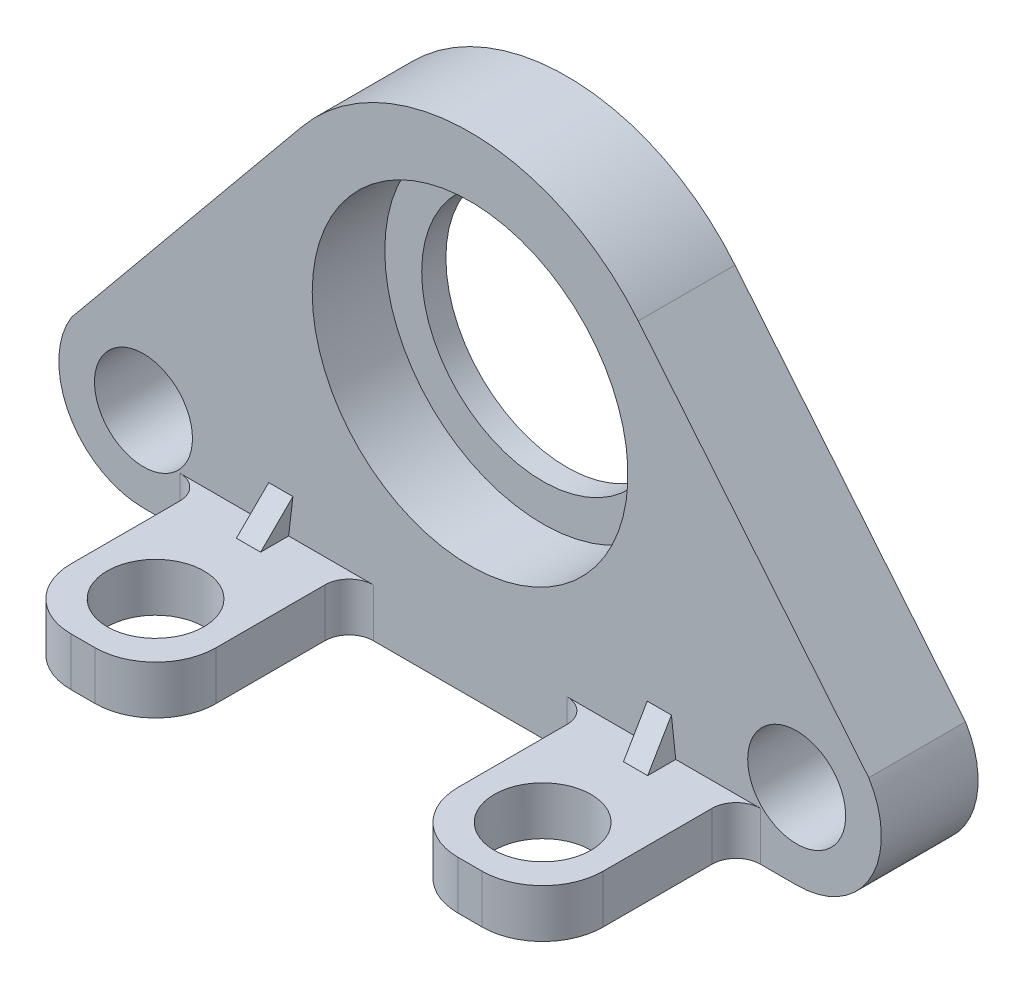
SolidWorks part; units mm, degrees
other "Triangulo"
other "lateral" parameters "D1"=39.9603, "D2"=11.6077, "D3"=8.4742, "D4"=1.8044
ref_plane "Alzado" through (0, 0, 0) normal (0, 0, 1) x (1, 0, 0)
ref_plane "Planta" through (0, 0, 0) normal (0, 1, 0) x (1, 0, 0)
ref_plane "Vista lateral" through (0, 0, 0) normal (1, 0, 0) x (0, 0, -1)
sketch "Croquis1" plane through (0, 0, 0) normal (0, 0, 1) x (1, 0, 0)
  line L0 (-7.4893, 0) -> (7.4893, 0)
  line L1 (-7.4893, 0) -> (0.0007, 21.6199)
  line L2 (0.0007, 21.6199) -> (7.4893, 0)
  line L3 (0, -7.4828) -> (0, 20.2315) construction
  dimension "D1" = 14.9787
  dimension "D2" = 21.6199
extrude "Saliente-Extruir1" add sketch "Croquis1" along normal mid plane 46
sketch "Croquis2" plane through (0, 0, 23) normal (0, 0, 1) x (1, 0, 0)
  line L0 (0, 0) -> (0, 22.9126) construction
  line L1 (37.4468, 0) -> (-37.4468, 0)
  line L2 (0.0007, 21.6199) -> (-37.4468, 0)
  line L3 (0.0007, 21.6199) -> (37.4468, 0)
  point P6 (0, 0)
  dimension "D1" = 74.8935
extrude "Saliente-Extruir2" add sketch "Croquis2" along normal blind 2
mirror "Simetría1" about plane through (0, 0, 0) normal (0, 0, 1) of "Saliente-Extruir2"
sketch "Croquis3" plane through (0, 0, 0) normal (0, -1, 0) x (1, 0, 0)
  line L1 (-37.4468, 25) -> (37.4468, 25)
  line L2 (-37.4468, 25) -> (-37.4468, -25)
  line L3 (-37.4468, -25) -> (37.4468, -25)
  line L4 (37.4468, 25) -> (37.4468, -25)
extrude "Saliente-Extruir3" add sketch "Croquis3" along normal blind 2 contours L2 L3 L4 L1
sketch "Croquis4" plane through (0, 0, 25) normal (0, 0, 1) x (1, 0, 0)
  line L0 (0, -2) -> (0, -6.2) construction
  line L1 (-37.4468, -2) -> (37.4468, -2) construction
  line L5 (7.7435, -2) -> (-7.7435, -2)
  circle A0 centre (0, -6.2) radius 4.05
  arc A1 (5.8197, -4.5466) -> (-5.8197, -4.5466) centre (0, -6.2) cw
  arc A2 (-5.8197, -4.5466) -> (-7.7435, -2) centre (-7.7435, -4) ccw
  arc A3 (5.8197, -4.5466) -> (7.7435, -2) centre (7.7435, -4) cw
  dimension "D2" = 8.1
  dimension "D4" = 2
  dimension "D1" = 4.2
  dimension "D3" = 2
extrude "Saliente-Extruir4" add sketch "Croquis4" against normal up to surface (50 mm away) contours A0
chamfer "Chaflán2" distance 1 angle 45 2 edges at (4.05, -6.2, 25) (4.05, -6.2, -25)
sketch "Croquis6" plane through (0, 0, -25) normal (0, 0, -1) x (-1, 0, 0)
  line L12 (-13.9105, 17.8924) -> (-35.5298, -19.554)
  line L13 (-35.5298, -19.554) -> (-34.5298, -21.2861)
  line L14 (-34.5298, -21.2861) -> (-8.8061, -6.4345)
  line L15 (4.6061, 1.3091) -> (30.3298, 16.1607)
  line L16 (30.3298, 16.1607) -> (29.3298, 17.8927)
  line L17 (29.3298, 17.8927) -> (-13.9105, 17.8924)
  circle A2 centre (0, -6.2) radius 4.05
  arc A6 (-5.8667, -7.6779) -> (-8.8061, -6.4345) centre (-7.8061, -8.1665) ccw
  arc A7 (-5.8667, -7.6779) -> (4.2133, -1.8583) centre (0, -6.2) ccw
  arc A8 (4.6061, 1.3091) -> (4.2133, -1.8583) centre (5.6061, -0.423) ccw
sketch "Croquis7" plane through (0, 0, -25) normal (0, 0, -1) x (-1, 0, 0)
  line L0 (-34.5298, -21.2861) -> (-8.8061, -6.4345) construction
  line L1 (0, -32.3279) -> (0, 26.7412) construction
  line L2 (27, -28.6153) -> (-27, -28.6153)
  line L3 (-13.9032, 5.2324) -> (-32.9573, -17.9396)
  line L5 (13.9032, 5.2324) -> (32.9573, -17.9396)
  circle A0 centre (-27, -21.6153) radius 4.05
  circle A1 centre (0, -6.2) radius 4.05 construction
  circle A2 centre (27, -21.6153) radius 4.05
  arc A3 (13.9032, 5.2324) -> (-13.9032, 5.2324) centre (0, -6.2) ccw
  arc A4 (-27, -28.6153) -> (-32.9573, -17.9396) centre (-27, -21.6153) cw
  arc A5 (27, -28.6153) -> (32.9573, -17.9396) centre (27, -21.6153) ccw
  circle A6 centre (0, -6.2) radius 13.05
  dimension "D1" = 8.1
  dimension "D2" = 27
  dimension "D3" = 7
  dimension "D4" = 18
  dimension "D6" = 26.1
  dimension "D5" = 30
extrude "Saliente-Extruir5" add sketch "Croquis7" along normal blind 6 separate body
sketch "Croquis8" plane through (0, 0, -25) normal (0, 0, 1) x (1, 0, 0)
  line L0 (27, -28.6153) -> (-27, -28.6153) construction
  line L1 (-22, -28.6153) -> (-10, -28.6153)
  line L2 (-22, -28.6153) -> (-22, -24.6153)
  line L3 (-22, -24.6153) -> (-10, -24.6153)
  line L4 (-10, -28.6153) -> (-10, -24.6153)
  line L5 (0, 11.8) -> (0, -38.4199) construction
  line L6 (22, -24.6153) -> (10, -24.6153)
  line L7 (10, -28.6153) -> (10, -24.6153)
  line L8 (22, -28.6153) -> (10, -28.6153)
  line L9 (22, -28.6153) -> (22, -24.6153)
  arc A0 (13.9032, 5.2324) -> (-13.9032, 5.2324) centre (0, -6.2) ccw construction
  dimension "D1" = 12
  dimension "D2" = 4
  dimension "D3" = 10
extrude "Saliente-Extruir6" add sketch "Croquis8" along normal blind 16
fillet "Redondeo3" radius 2 4 edges at (22, -26.6153, -25) (10, -26.6153, -25) (-10, -26.6153, -25) (-22, -26.6153, -25)
fillet "Redondeo4" radius 5 4 edges at (22, -26.6153, -9) (10, -26.6153, -9) (-22, -26.6153, -9) (-10, -26.6153, -9)
sketch "Croquis14" plane through (0, -24.6153, 0) normal (0, 1, 0) x (1, 0, 0)
  line L0 (0, 0) -> (0, 45.0228) construction
  line L1 (-22, 14) -> (-22, 23) construction
  line L2 (-15, 9) -> (-17, 9) construction
  circle A0 centre (-16, 15) radius 4
  circle A1 centre (16, 15) radius 4
  dimension "D1" = 6
  dimension "D2" = 6
  dimension "D3" = 8
extrude "Cortar-Extruir1" cut sketch "Croquis14" against normal blind 10 contours A0 | A1
sketch "Croquis16" plane through (0, -24.6153, 0) normal (0, 1, 0) x (1, 0, 0)
  line L0 (-16, 25) -> (-16, 22.6812)
  line L1 (-8, 25) -> (-24, 25) construction
sketch3d "Croquis3D2"
  line L0 (-27, -21.6153, -25) -> (-4.2911, -21.6153, -25) construction
  line L1 (-27, -21.6153, -31) -> (-27, -21.6153, -25) construction
  line L2 (-16, -24.6153, -22.6812) -> (-15.6455, -21.6153, -25)
  line L3 (-16, -24.6153, -22.6812) -> (-16, -24.6153, -25)
  line L4 (-16, -24.6153, -25) -> (-15.6455, -21.6153, -25)
extrude "Saliente-Extruir7" add sketch "Croquis3D2" along direction (1, 0, 0) on the side of the normal mid plane 2 contours L2 L4 L3
mirror "Simetría2" about plane through (0, 0, 0) normal (1, 0, 0) of "Saliente-Extruir7"
sketch "Croquis20" plane through (0, 0, -31) normal (0, 0, -1) x (-1, 0, 0)
  line L3 (32.9573, -17.9396) -> (13.9032, 5.2324)
  line L4 (-13.9032, 5.2324) -> (-32.9573, -17.9396)
  line L5 (-27, -28.6153) -> (27, -28.6153)
  line L6 (32.9573, -17.9396) -> (13.9032, 5.2324)
  line L7 (-13.9032, 5.2324) -> (-32.9573, -17.9396)
  line L8 (-27, -28.6153) -> (27, -28.6153)
  circle A0 centre (-27, -21.6153) radius 4.05 construction
  circle A1 centre (-27, -21.6153) radius 4.05
  circle A2 centre (27, -21.6153) radius 4.05 construction
  arc A3 (27, -28.6153) -> (32.9573, -17.9396) centre (27, -21.6153) ccw
  arc A4 (13.9032, 5.2324) -> (-13.9032, 5.2324) centre (0, -6.2) ccw
  arc A5 (-32.9573, -17.9396) -> (-27, -28.6153) centre (-27, -21.6153) ccw
  arc A6 (27, -28.6153) -> (32.9573, -17.9396) centre (27, -21.6153) ccw
  arc A7 (13.9032, 5.2324) -> (-13.9032, 5.2324) centre (0, -6.2) ccw
  arc A8 (-32.9573, -17.9396) -> (-27, -28.6153) centre (-27, -21.6153) ccw
  circle A9 centre (27, -21.6153) radius 4.05
  circle A10 centre (0, -6.2) radius 10
  dimension "D2" = 20
  dimension "D1" = 0
extrude "Saliente-Extruir8" add sketch "Croquis20" along normal blind 2
chamfer "Chaflán3" distance 1 angle 45 2 edges at (22.95, -21.6153, -33) (-31.05, -21.6153, -33)
delete or keep bodies "Sólido-Eliminar/Conservar 1" type delete bodies bodies 105
equation "\"B\"= 74.8935"
equation "\"h\"= 21.6199"
equation "\"an\"= 30°"
equation "\"w\"=4"
equation "\"z\"= 2"
equation "\"p\"= 50"
equation "\"r\"= 8"
equation "\"base\"= \"B\" / 5"
equation "\"D1@Croquis1\"=\"base\""
equation "\"D2@Croquis1\"=\"h\""
equation "\"D1@Saliente-Extruir1\"=\"p\"-2*\"z\""
equation "\"D1@Croquis2\"=\"B\""
equation "\"D1@Croquis4\"=\"w\"+0.2"
